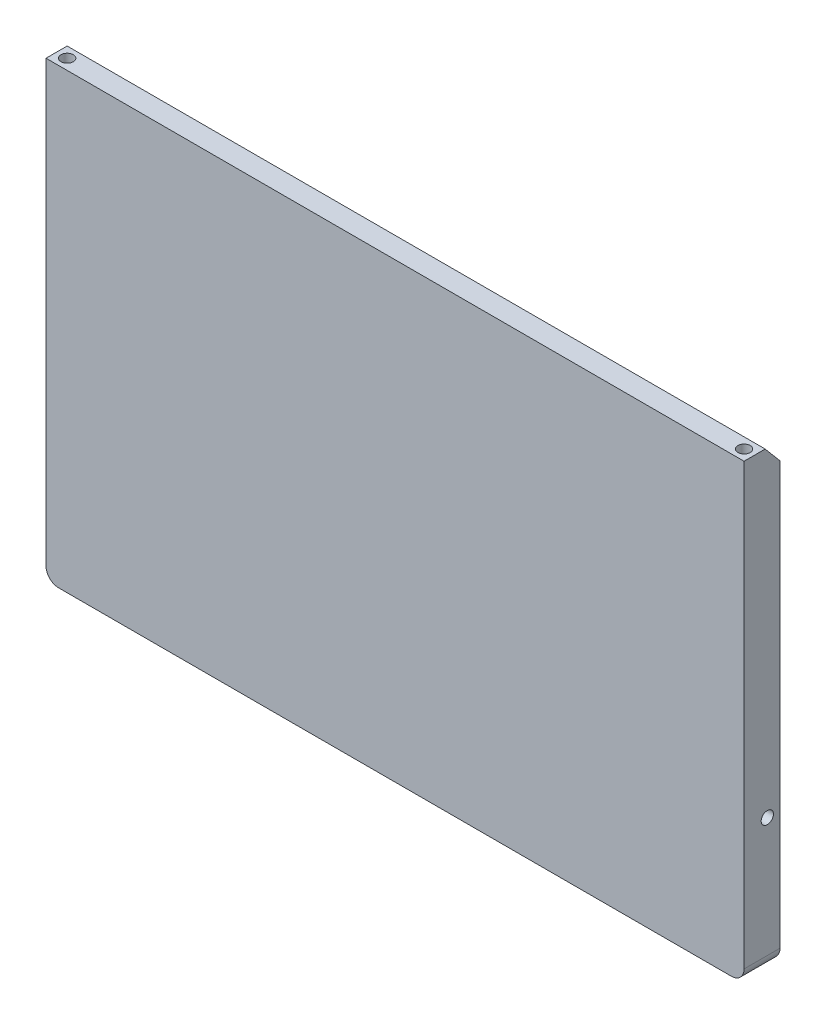
SolidWorks part; units mm, degrees
material "PLA"
ref_plane "Front Plane" through (0, 0, 0) normal (0, 0, 1) x (1, 0, 0)
ref_plane "Top Plane" through (0, 0, 0) normal (0, 1, 0) x (1, 0, 0)
ref_plane "Right Plane" through (0, 0, 0) normal (1, 0, 0) x (0, 0, -1)
sketch "Sketch1" plane through (0, 0, 0) normal (0, 0, 1) x (1, 0, 0)
  line L0 (0, 0) -> (0, -138.8145) construction
  line L1 (-82.55, -80.8019) -> (82.55, -80.8019)
  line L2 (-82.55, -80.8019) -> (-82.55, 9.1981)
  line L3 (-82.55, 9.1981) -> (82.55, 9.1981)
  line L4 (82.55, -80.8019) -> (82.55, 9.1981)
  point P7 (0, -80.8019)
  dimension "D1" = 165.1
  dimension "D2" = 90
extrude "Boss-Extrude1" add sketch "Sketch1" along normal blind 5
sketch "Sketch2" plane through (0, 9.1981, 0) normal (0, 1, 0) x (1, 0, 0)
  line L0 (-82.55, -5) -> (-82.55, 0) construction
  line L1 (82.55, -5) -> (82.55, 0) construction
  circle A0 centre (-80.05, -2.5) radius 1.45
  circle A1 centre (80.05, -2.5) radius 1.45
  point P7 (-82.55, -2.5)
  dimension "D2" = 2.9
  dimension "D4" = 2.9
  dimension "D1" = 2.5
  dimension "D3" = 2.5
extrude "Cut-Extrude1" cut sketch "Sketch2" against normal blind 7 contours A1 | A0
sketch "Sketch4" plane through (0, 0, 0) normal (0, 0, -1) x (-1, 0, 0)
  line L4 (-82.55, 9.1981) -> (-82.55, -80.8019)
  line L5 (-82.55, -80.8019) -> (82.55, -80.8019)
  line L6 (82.55, -80.8019) -> (82.55, 9.1981)
  line L7 (82.55, 9.1981) -> (-82.55, 9.1981)
  line L8 (-82.55, 9.1981) -> (-82.55, -80.8019)
  line L9 (-82.55, -80.8019) -> (82.55, -80.8019)
  line L10 (82.55, -80.8019) -> (82.55, 9.1981)
  line L11 (82.55, 9.1981) -> (-82.55, 9.1981)
  dimension "D1" = 0
extrude "Boss-Extrude2" add sketch "Sketch4" along normal blind 3.5
sketch "Sketch5" plane through (0, 0, -3.5) normal (0, 0, -1) x (-1, 0, 0)
  line L0 (0, 9.1981) -> (0, -80.8019) construction
  line L1 (-50.1, 3.7981) -> (50.1, 3.7981)
  line L2 (-50.1, 3.7981) -> (-50.1, -75.4019)
  line L3 (-50.1, -75.4019) -> (50.1, -75.4019)
  line L4 (50.1, 3.7981) -> (50.1, -75.4019)
  line L5 (82.55, 9.1981) -> (-82.55, 9.1981) construction
  line L6 (-82.55, -80.8019) -> (82.55, -80.8019) construction
  point P10 (0, 3.7981)
  point P11 (-50.1, -35.8019)
  point P12 (0, -35.8019)
  dimension "D1" = 100.2
  dimension "D2" = 79.2
chamfer "Chamfer1" distance 3.5 angle 50 1 edges at (0, 9.1981, -3.5)
ref_plane "Plane1" through (-27.79, 0, 0) normal (-1, 0, 0) x (0, 0, 1)
extrude "Cut-Extrude3" cut sketch "Sketch5" against normal blind 6.5
sketch "Sketch8" plane through (82.55, 0, 0) normal (1, 0, 0) x (0, 0, -1)
  line L2 (0.5, -68.0019) -> (0.5, -65.1019) construction
  circle A2 centre (0.5, -66.5519) radius 1.45
extrude "Cut-Extrude5" cut sketch "Sketch8" against normal blind 3
mirror "Mirror2" about plane through (0, 0, 0) normal (1, 0, 0) of "Cut-Extrude5"
sketch "Sketch10" plane through (0, -80.8019, 0) normal (0, -1, 0) x (1, 0, 0)
  line L4 (-82.55, 5) -> (-82.55, -3.5)
  line L5 (-82.55, -3.5) -> (82.55, -3.5)
  line L6 (82.55, -3.5) -> (82.55, 5)
  line L7 (82.55, 5) -> (-82.55, 5)
  line L8 (-82.55, 5) -> (-82.55, -3.5)
  line L9 (-82.55, -3.5) -> (82.55, -3.5)
  line L10 (82.55, -3.5) -> (82.55, 5)
  line L11 (82.55, 5) -> (-82.55, 5)
  dimension "D1" = 0
extrude "Boss-Extrude4" add sketch "Sketch10" along normal blind 17
fillet "Fillet1" radius 3 2 edges at (82.55, -97.8019, 0.75) (-82.55, -97.8019, 0.75)
